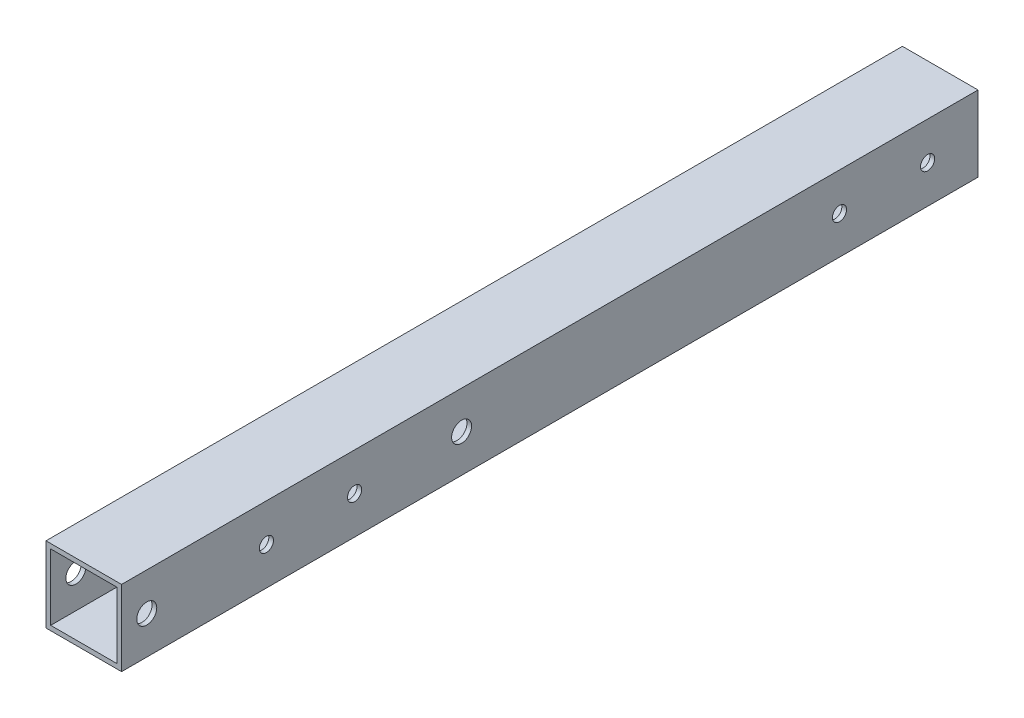
SolidWorks part; units mm, degrees
material "Plain Carbon Steel"
ref_plane "Front Plane" through (0, 0, 0) normal (0, 0, 1) x (1, 0, 0)
ref_plane "Top Plane" through (0, 0, 0) normal (0, 1, 0) x (1, 0, 0)
ref_plane "Right Plane" through (0, 0, 0) normal (1, 0, 0) x (0, 0, -1)
sketch "Sketch1" plane through (0, 0, 0) normal (0, 0, 1) x (1, 0, 0)
  line L1 (-19.05, -19.05) -> (19.05, -19.05)
  line L2 (-19.05, -19.05) -> (-19.05, 19.05)
  line L3 (-19.05, 19.05) -> (19.05, 19.05)
  line L4 (19.05, -19.05) -> (19.05, 19.05)
  line L5 (-19.05, -19.05) -> (19.05, 19.05) construction
  line L6 (-19.05, 19.05) -> (19.05, -19.05) construction
  line L7 (-16.6878, -16.6878) -> (16.6878, -16.6878)
  line L8 (-16.6878, -16.6878) -> (-16.6878, 16.6878)
  line L9 (-16.6878, 16.6878) -> (16.6878, 16.6878)
  line L10 (16.6878, -16.6878) -> (16.6878, 16.6878)
  line L11 (-16.6878, -16.6878) -> (16.6878, 16.6878) construction
  line L12 (-16.6878, 16.6878) -> (16.6878, -16.6878) construction
  point P0 (0, 0)
  point P6 (0, 0)
  dimension "D1" = 2.3622
  dimension "D2" = 38.1
extrude "Extrude1" add sketch "Sketch1" along normal blind 431.8
sketch "Sketch2" plane through (19.05, 0, 0) normal (1, 0, 0) x (0, 0, -1)
  line L0 (-431.8, 0) -> (-419.1, 0) construction
  line L1 (-431.8, -19.05) -> (-431.8, 19.05) construction
  line L2 (-419.1, 0) -> (-358.775, 0) construction
  line L3 (-358.775, 0) -> (-314.325, 0) construction
  line L4 (-314.325, 0) -> (-69.85, 0) construction
  line L5 (-69.85, 0) -> (-25.4, 0) construction
  line L6 (0, -19.05) -> (0, 19.05) construction
  line L7 (-431.8, 0) -> (-260.35, 0) construction
  point P5 (0, 0)
  dimension "D1" = 12.7
  dimension "D2" = 25.4
  dimension "D3" = 288.925
  dimension "D4" = 44.45
  dimension "D5" = 171.45
hole_wizard "1/4 Clearance Hole1" positions "3DSketch1" profile "Sketch4" hole size "1/4" standard "Ansi Inch" end condition through all
sketch3d "3DSketch1"
  point P0 (19.05, 0, 358.775)
  point P3 (19.05, 0, 314.325)
  point P6 (19.05, 0, 69.85)
  point P9 (19.05, 0, 25.4)
sketch "Sketch4" plane through (19.05, 0, 358.775) normal (0, 1, 0) x (0, 0, -1)
  line L0 (0, 0) -> (0, 38.1)
  line L1 (0, 38.1) -> (3.5712, 38.1)
  line L2 (3.5712, 38.1) -> (3.5712, 0)
  line L5 (3.5712, 0) -> (0, 0)
  line L11 (0, -6.35) -> (0, 107.95) construction
  dimension "Thru Hole Dia." = 7.1425
  dimension "Thru Hole Depth" = 38.1
hole_wizard "3/8 Clearance Hole1" positions "3DSketch2" profile "Sketch5" hole size "3/8" standard "Ansi Inch" end condition through all
sketch3d "3DSketch2"
  point P0 (19.05, 0, 419.1)
  point P3 (19.05, 0, 260.35)
sketch "Sketch5" plane through (19.05, 0, 419.1) normal (0, 1, 0) x (0, 0, -1)
  line L0 (0, 0) -> (0, 38.1)
  line L1 (0, 38.1) -> (5.0419, 38.1)
  line L2 (5.0419, 38.1) -> (5.0419, 0)
  line L5 (5.0419, 0) -> (0, 0)
  line L11 (0, -6.35) -> (0, 107.95) construction
  dimension "Thru Hole Dia." = 10.0838
  dimension "Thru Hole Depth" = 38.1
